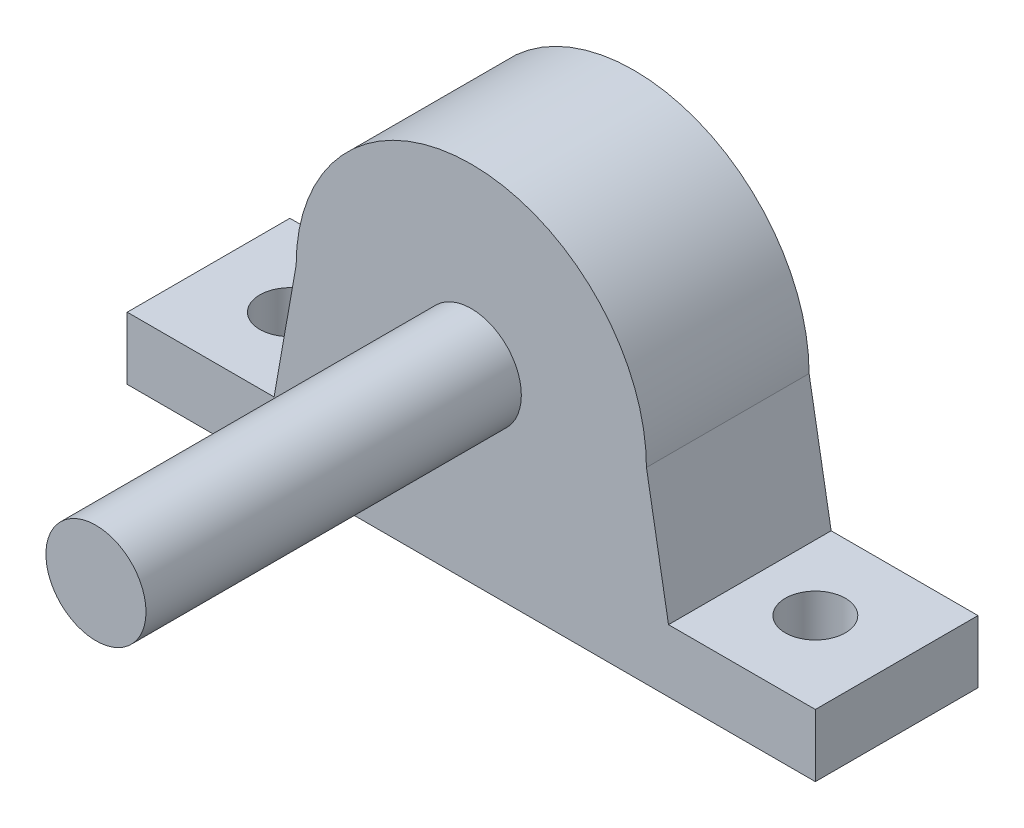
SolidWorks part; units mm, degrees
ref_plane "前视基准面" through (0, 0, 0) normal (0, 0, 1) x (1, 0, 0)
ref_plane "上视基准面" through (0, 0, 0) normal (0, 1, 0) x (1, 0, 0)
ref_plane "右视基准面" through (0, 0, 0) normal (1, 0, 0) x (0, 0, -1)
sketch "草图1" plane through (0, 0, 0) normal (0, 0, 1) x (1, 0, 0)
  line L0 (0, 0) -> (55, 0)
  line L1 (0, 0) -> (0, 5)
  line L2 (0, 5) -> (11.7367, 5)
  line L3 (55, 5) -> (55, 0)
  line L4 (-3.5544, 15) -> (61.7971, 15) construction
  line L5 (27.5, 0) -> (27.5, 32.9563) construction
  line L6 (13.5, 15) -> (11.7367, 5)
  line L7 (41.5, 15) -> (43.2633, 5)
  line L8 (43.2633, 5) -> (55, 5)
  arc A0 (27.5, 1) -> (37.298, 5) centre (27.5, 15) ccw construction
  arc A1 (41.5, 15) -> (13.5, 15) centre (27.5, 15) ccw
  dimension "D4" = 28
  dimension "D1" = 55
  dimension "D2" = 5
  dimension "D3" = 15
  dimension "D5" = 10
extrude "凸台-拉伸1" add sketch "草图1" along normal blind 13
sketch "草图2" plane through (0, 0, 13) normal (0, 0, 1) x (1, 0, 0)
  circle A0 centre (27.5, 15) radius 4
  dimension "D1" = 8
extrude "切除-拉伸1" cut sketch "草图2" against normal blind 13
sketch "草图3" plane through (0, 5, 0) normal (0, 1, 0) x (1, 0, 0)
  line L0 (0, -6.5) -> (55, -6.5) construction
  line L1 (0, -13) -> (0, 0) construction
  line L2 (55, -13) -> (55, 0) construction
  line L3 (27.5, 0) -> (27.5, -13) construction
  line L4 (41.5, 0) -> (13.5, 0) construction
  line L5 (13.5, -13) -> (41.5, -13) construction
  circle A0 centre (6.5, -6.5) radius 2.4
  circle A1 centre (48.5, -6.5) radius 2.4
  point P16 (27.5, -6.5)
  dimension "D3" = 4.8
  dimension "D4" = 4.8
  dimension "D1" = 21
  dimension "D2" = 21
extrude "切除-拉伸2" cut sketch "草图3" against normal up to next
sketch "草图4" plane through (0, 0, 13) normal (0, 0, 1) x (1, 0, 0)
  circle A0 centre (27.5, 15) radius 4 construction
  circle A1 centre (27.5, 15) radius 4
extrude "凸台-拉伸2" add sketch "草图4" along normal blind 30 and the other way blind 13
